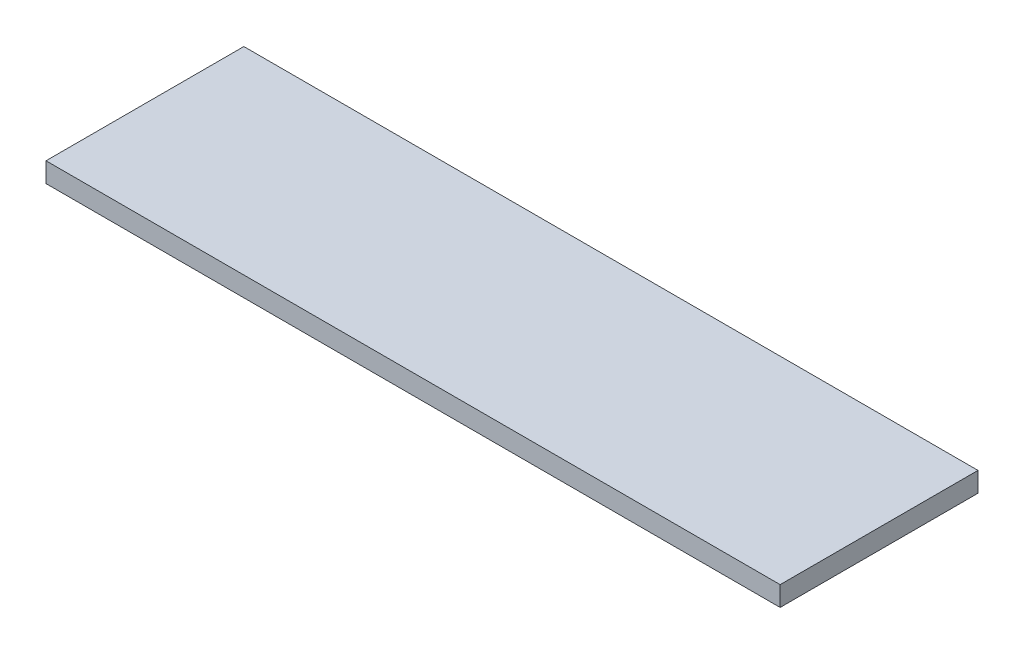
SolidWorks part; units mm, degrees
material "AISI 1020"
ref_plane "Front Plane" through (0, 0, 0) normal (0, 0, 1) x (1, 0, 0)
ref_plane "Top Plane" through (0, 0, 0) normal (0, 1, 0) x (1, 0, 0)
ref_plane "Right Plane" through (0, 0, 0) normal (1, 0, 0) x (0, 0, -1)
sketch "Sketch1" plane through (0, 0, 0) normal (0, 1, 0) x (1, 0, 0)
  line L1 (-150.6285, -16.5202) -> (99.3715, -16.5202)
  line L2 (-150.6285, -16.5202) -> (-150.6285, -56.5202)
  line L3 (-150.6285, -56.5202) -> (99.3715, -56.5202)
  line L4 (99.3715, -16.5202) -> (99.3715, -56.5202)
  dimension "D1" = 40
  dimension "D2" = 250
extrude "Boss-Extrude1" add sketch "Sketch1" along normal blind 4
sketch "Sketch4" plane through (0, 0, 0) normal (0, -1, 0) x (1, 0, 0)
  line L0 (-46.0498, 16.5202) -> (-46.0498, 196.5202) construction
  line L1 (-49.0498, 61.5878) -> (-175.9977, 61.5878)
  line L2 (-49.0498, 61.5878) -> (-49.0498, 8.3297)
  line L3 (-49.0498, 8.3297) -> (-175.9977, 8.3297)
  line L4 (-175.9977, 61.5878) -> (-175.9977, 8.3297)
  dimension "D1" = 3
extrude "Cut-Extrude3" cut sketch "Sketch4" against normal blind 10
